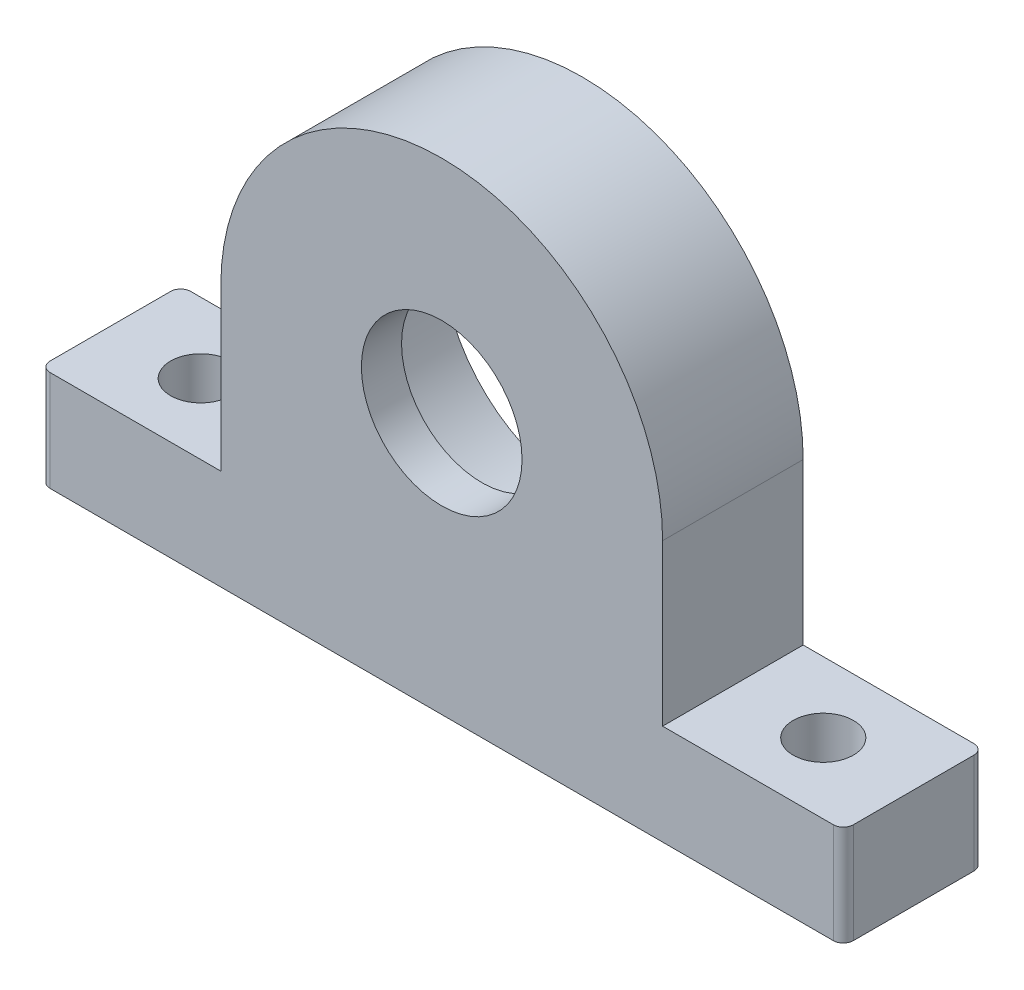
SolidWorks part; units mm, degrees
ref_plane "Front Plane" through (0, 0, 0) normal (0, 0, 1) x (1, 0, 0)
ref_plane "Top Plane" through (0, 0, 0) normal (0, 1, 0) x (1, 0, 0)
ref_plane "Right Plane" through (0, 0, 0) normal (1, 0, 0) x (0, 0, -1)
sketch "Sketch1" plane through (0, 0, 0) normal (0, 0, 1) x (1, 0, 0)
  line L0 (-11, 0) -> (-11, -8)
  line L1 (-11, -8) -> (-20, -8)
  line L2 (-20, -8) -> (-20, -13)
  line L3 (-20, -13) -> (20, -13)
  line L4 (0, 11) -> (0, -13) construction
  line L5 (11, -8) -> (20, -8)
  line L6 (20, -8) -> (20, -13)
  line L7 (11, 0) -> (11, -8)
  circle A0 centre (0, 0) radius 4
  circle A1 centre (0, 0) radius 11
  dimension "D1" = 8
  dimension "D2" = 22
  dimension "D3" = 5
  dimension "D4" = 20
  dimension "D5" = 13
extrude "Boss-Extrude1" add sketch "Sketch1" along normal blind 7 contours L4 A1 A0 | L4 A1 L0 L1 L2 L3 | A1 L4 L3 L6 L5 L7 | A1 L4 A0
sketch "Sketch2" plane through (0, 0, 0) normal (0, 0, -1) x (-1, 0, 0)
  circle A0 centre (0, 0) radius 7
  dimension "D1" = 14
extrude "Cut-Extrude1" cut sketch "Sketch2" against normal blind 5
sketch "Sketch3" plane through (0, -8, 0) normal (0, 1, 0) x (1, 0, 0)
  line L0 (0, 4.0963) -> (0, -14.2006) construction
  line L1 (-20, -3.5) -> (20, -3.5) construction
  line L2 (20, -7) -> (20, 0) construction
  line L3 (-20, -7) -> (-20, 0) construction
  circle A0 centre (-15.5, -3.5) radius 1.5
  circle A2 centre (15.5, -3.5) radius 1.5
  dimension "D1" = 3
  dimension "D2" = 15.5
extrude "Cut-Extrude2" cut sketch "Sketch3" against normal blind 5
fillet "Fillet1" radius 0.5 4 edges at (20, -10.5, 7) (20, -10.5, 0) (-20, -10.5, 7) (-20, -10.5, 0)
